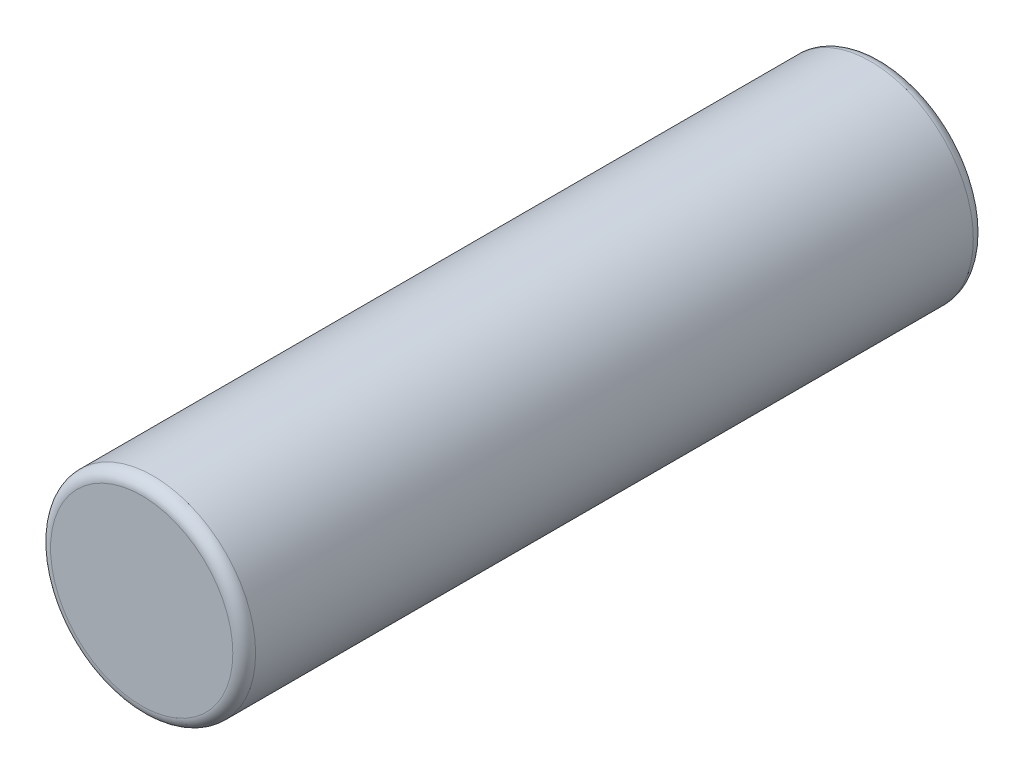
SolidWorks part; units mm, degrees
ref_plane "Plano frontal" through (0, 0, 0) normal (0, 0, 1) x (1, 0, 0)
ref_plane "Plano superior" through (0, 0, 0) normal (0, 1, 0) x (1, 0, 0)
ref_plane "Plano direito" through (0, 0, 0) normal (1, 0, 0) x (0, 0, -1)
sketch "Esboço1" plane through (0, 0, 0) normal (0, 0, 1) x (1, 0, 0)
  circle A0 centre (0, 0) radius 9
  dimension "D1" = 18
extrude "Ressalto-extrusão1" add sketch "Esboço1" along normal blind 65
fillet "Filete2" radius 1 2 edges at (9, 0, 0) (9, 0, 65)
